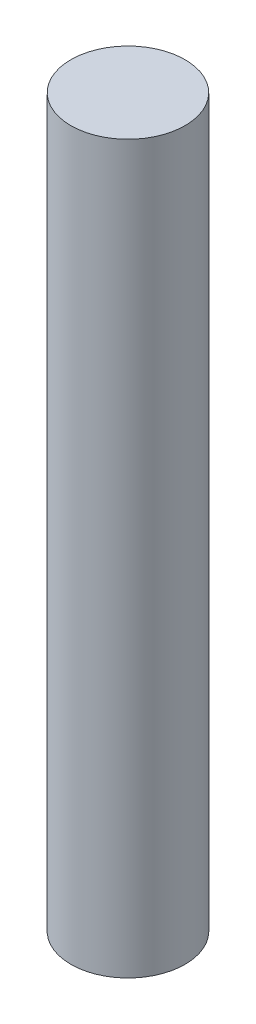
SolidWorks part; units mm, degrees
ref_plane "Front Plane" through (0, 0, 0) normal (0, 0, 1) x (1, 0, 0)
ref_plane "Top Plane" through (0, 0, 0) normal (0, 1, 0) x (1, 0, 0)
ref_plane "Right Plane" through (0, 0, 0) normal (1, 0, 0) x (0, 0, -1)
sketch "Sketch1" plane through (0, 0, 0) normal (0, 1, 0) x (1, 0, 0)
  circle A0 centre (0, 0) radius 3.175
  dimension "D1" = 6.35
sketch "Sketch2" plane through (0, 0, 0) normal (1, 0, 0) x (0, 0, -1)
  line L0 (0, 0) -> (0, 40.3646)
  circle A0 centre (0, 0) radius 40.3646 construction
extrude "Boss-Extrude1" add sketch "Sketch1" along normal up to vertex (40.3646 mm away) contours A0 up to point (0, 40.3646, 0)
